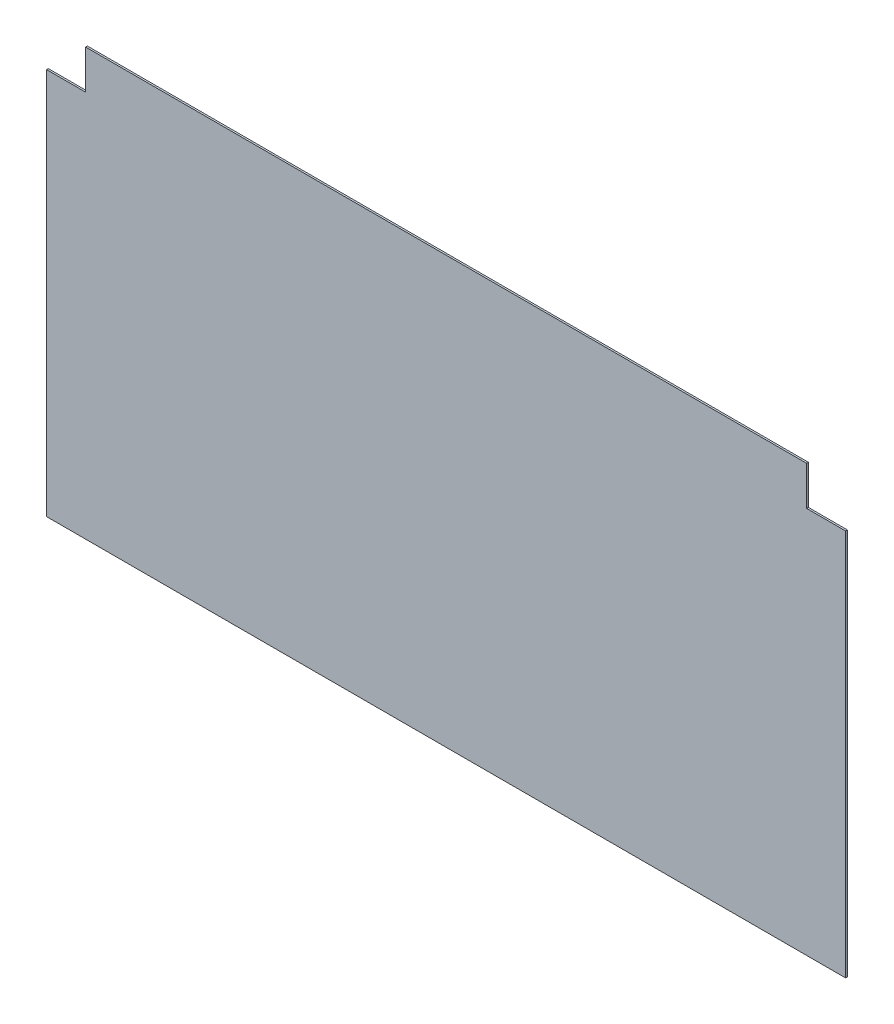
SolidWorks part; units mm, degrees
material "1345 Alloy"
ref_plane "Front Plane" through (0, 0, 0) normal (0, 0, 1) x (1, 0, 0)
ref_plane "Top Plane" through (0, 0, 0) normal (0, 1, 0) x (1, 0, 0)
ref_plane "Right Plane" through (0, 0, 0) normal (1, 0, 0) x (0, 0, -1)
sketch "Sketch1" plane through (0, 0, 0) normal (0, 0, 1) x (1, 0, 0)
  line L1 (-225, 120) -> (225, 120)
  line L2 (-225, 120) -> (-225, -120)
  line L3 (-225, -120) -> (225, -120)
  line L4 (225, 120) -> (225, -120)
  line L5 (-225, 120) -> (225, -120) construction
  line L6 (-225, -120) -> (225, 120) construction
  point P0 (0, 0)
  dimension "D1" = 450
  dimension "D2" = 240
extrude "Boss-Extrude1" add sketch "Sketch1" along normal blind 1
sketch "Sketch2" plane through (0, 0, 1) normal (0, 0, 1) x (1, 0, 0)
  line L1 (-225, 120) -> (-203, 120)
  line L2 (-225, 120) -> (-225, 98)
  line L3 (-225, 98) -> (-203, 98)
  line L4 (-203, 120) -> (-203, 98)
  line L5 (225, 120) -> (203, 120)
  line L6 (225, 120) -> (225, 98)
  line L7 (225, 98) -> (203, 98)
  line L8 (203, 120) -> (203, 98)
  dimension "D1" = 22
  dimension "D2" = 22
  dimension "D3" = 22
  dimension "D4" = 22
extrude "Cut-Extrude1" cut sketch "Sketch2" against normal blind 10
